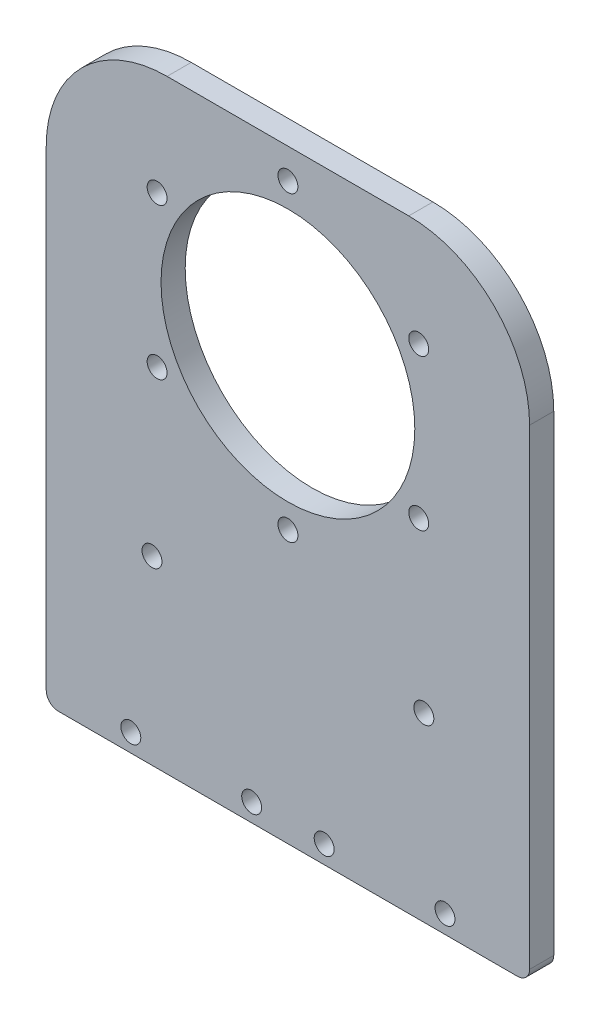
SolidWorks part; units mm, degrees
material "玻纤板"
ref_plane "前视基准面" through (0, 0, 0) normal (0, 0, 1) x (1, 0, 0)
ref_plane "上视基准面" through (0, 0, 0) normal (0, 1, 0) x (1, 0, 0)
ref_plane "右视基准面" through (0, 0, 0) normal (1, 0, 0) x (0, 0, -1)
other "Configuration Table"
sketch "草图1" plane through (0, 0, 0) normal (0, 0, 1) x (1, 0, 0)
  line L1 (-40, 50) -> (40, 50)
  line L2 (-40, 50) -> (-40, -50)
  line L3 (-40, -50) -> (40, -50)
  line L4 (40, 50) -> (40, -50)
  line L5 (-40, 50) -> (40, -50) construction
  line L6 (-40, -50) -> (40, 50) construction
  circle A0 centre (0, 45) radius 1.65
  circle A3 centre (0, 20) radius 25 construction
  circle A9 centre (21.6506, 32.5) radius 1.65
  circle A10 centre (21.6506, 7.5) radius 1.65
  circle A11 centre (0, -5) radius 1.65
  circle A12 centre (-21.6506, 7.5) radius 1.65
  circle A13 centre (-21.6506, 32.5) radius 1.65
  point P0 (0, 20)
  point P14 (0, 0)
  point P17 (0, 20)
  point P21 (0, 20)
  point P25 (0, 20)
  point P26 (0, 0)
  dimension "D3" = 3.3
  dimension "D6" = 50
  dimension "D7" = 70
  dimension "D1" = 80
  dimension "D2" = 25
  dimension "D5" = 100
  dimension "D4" = 6
extrude "凸台-拉伸1" add sketch "草图1" along normal blind 4
sketch "草图3" plane through (0, 0, 4) normal (0, 0, 1) x (1, 0, 0)
  circle A0 centre (0, 20) radius 25 construction
  circle A1 centre (0, 45) radius 1.65 construction
  circle A2 centre (0, 20) radius 21
  dimension "D2" = 42
  dimension "D1" = 25
extrude "切除-拉伸2" cut sketch "草图3" against normal through all
fillet "圆角1" radius 2 2 edges at (40, -50, 2) (-40, -50, 2)
sketch "草图2" plane through (0, 0, 4) normal (0, 0, 1) x (1, 0, 0)
  line L0 (0, 0) -> (0, 60.2079) construction
  line L1 (-38, -50) -> (38, -50) construction
  line L2 (-40, 50) -> (-40, -48) construction
  circle A0 centre (-26, -47) radius 1.65
  circle A1 centre (-6, -47) radius 1.65
  circle A2 centre (6, -47) radius 1.65
  circle A3 centre (26, -47) radius 1.65
  dimension "D2" = 3.3
  dimension "D3" = 3
  dimension "D1" = 20
  dimension "D4" = 14
extrude "切除-拉伸1" cut sketch "草图2" against normal through all
fillet "圆角2" radius 20 2 edges at (40, 50, 2) (-40, 50, 2)
sketch "草图4" plane through (0, 0, 4) normal (0, 0, 1) x (1, 0, 0)
  line L0 (-38, -50) -> (38, -50) construction
  line L1 (-40, 30) -> (-40, -48) construction
  line L2 (0, 20) -> (-55.4344, 20) construction
  line L3 (0, 20) -> (0, 67.7473) construction
  circle A0 centre (-22.5, -20) radius 1.65
  circle A1 centre (-22.5, 60) radius 1.65
  circle A2 centre (22.5, -20) radius 1.65
  circle A3 centre (22.5, 60) radius 1.65
  dimension "D1" = 30
  dimension "D2" = 17.5
  dimension "D3" = 3.3
extrude "切除-拉伸3" cut sketch "草图4" against normal through all
